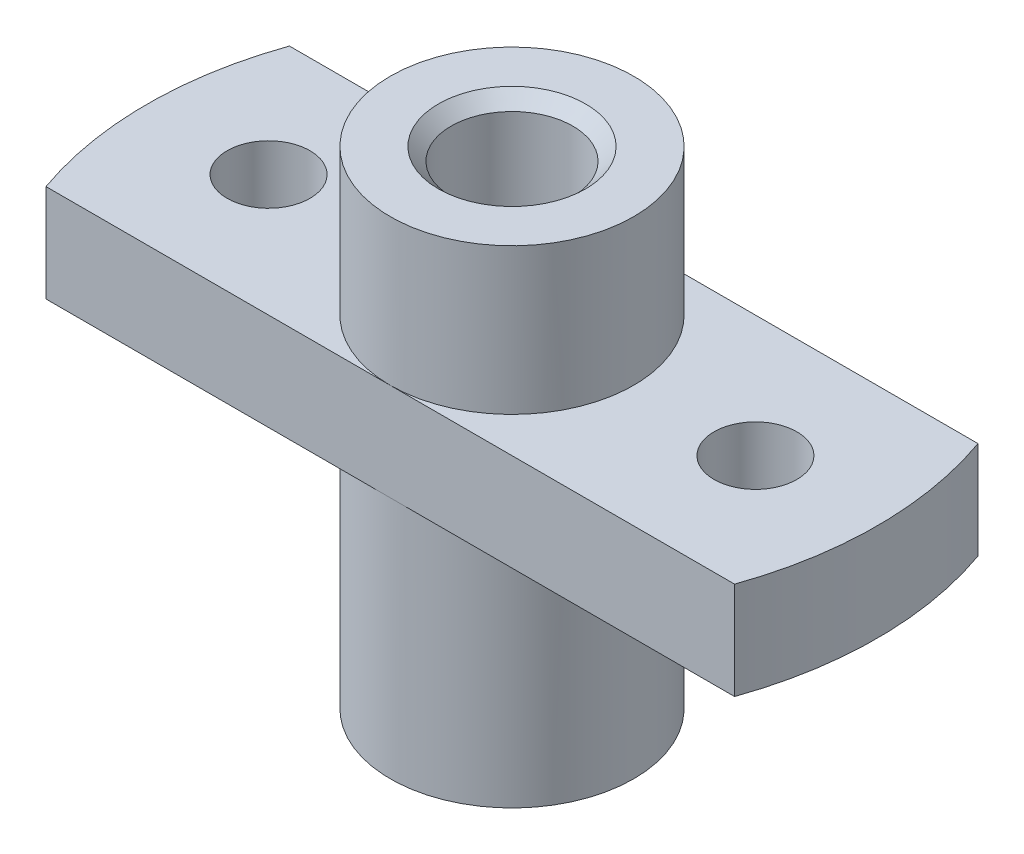
SolidWorks part; units mm, degrees
ref_plane "Front Plane" through (0, 0, 0) normal (0, 0, 1) x (1, 0, 0)
ref_plane "Top Plane" through (0, 0, 0) normal (0, 1, 0) x (1, 0, 0)
ref_plane "Right Plane" through (0, 0, 0) normal (1, 0, 0) x (0, 0, -1)
sketch "Sketch2" plane through (0, 0, 0) normal (0, 0, 1) x (1, 0, 0)
  line L0 (0, 0) -> (-5, 0)
  line L1 (-5, 0) -> (-5, 10)
  line L2 (-5, 10) -> (-15, 10)
  line L3 (-15, 10) -> (-15, 14)
  line L4 (-15, 14) -> (-5, 14)
  line L5 (-5, 14) -> (-5, 20)
  line L6 (-5, 20) -> (0, 20)
  line L7 (0, 20) -> (0, 0)
  dimension "D1" = 5
  dimension "D2" = 10
  dimension "D3" = 4
  dimension "D4" = 6
  dimension "D5" = 15
revolve "Revolve1" add sketch "Sketch2" angle 360 about L7
hole_wizard "M3 Clearance Hole1" positions "Sketch5" profile "Sketch4" hole size "M3" standard "ISO" end condition up to next
sketch "Sketch5" plane through (0, 14, 0) normal (0, 1, 0) x (-1, 0, 0)
  line L0 (-30.2348, 0) -> (30.2348, 0) construction
  line L2 (0, -14.7703) -> (0, 14.7703) construction
  point P0 (10, 0)
  point P15 (-10, 0)
  dimension "D1" = 20
sketch "Sketch4" plane through (-10, 14, 0) normal (1, 0, 0) x (0, 0, 1)
  line L0 (0, 0) -> (0, 4)
  line L1 (0, 4) -> (1.7, 4)
  line L2 (1.7, 4) -> (1.7, 0)
  line L5 (1.7, 0) -> (0, 0)
  line L11 (0, -6.35) -> (0, 107.95) construction
  dimension "Thru Hole Dia." = 3.4
  dimension "Thru Hole Depth" = 4
hole_wizard "M6 Tapped Hole1" positions "Sketch7" profile "Sketch8" tap size "M6" standard "ISO" end condition up to next
sketch "Sketch7" plane through (0, 20, 0) normal (0, 1, 0) x (-1, 0, 0)
  point P0 (0, 0)
sketch "Sketch8" plane through (0, 20, 0) normal (1, 0, 0) x (0, 0, 1)
  line L0 (0, 0) -> (0, 20)
  line L1 (0, 20) -> (3.025, 20)
  line L2 (2.5, 19.475) -> (2.5, 0.525)
  line L3 (2.5, 0.525) -> (3.025, 0)
  line L5 (3.025, 0) -> (0, 0)
  line L6 (-2.5, 0.525) -> (-3.025, 0) construction
  line L7 (3.025, 20) -> (2.5, 19.475)
  line L8 (-3.025, 20) -> (-2.5, 19.475) construction
  line L11 (0, -6.35) -> (0, 107.95) construction
  dimension "Thru Tap Drill Dia." = 5
  dimension "Thru Tap Drill Depth" = 20
  dimension "Near C'Sink Dia." = 6.05
  dimension "Near C'Sink Angle" = 90
  dimension "Far C'Sink Dia." = 6.05
  dimension "Far C'Sink Angle" = 90
cosmetic thread "Hole Thread1" parameters "D2"=6
sketch "Sketch9" plane through (0, 14, 0) normal (0, 1, 0) x (1, 0, 0)
  line L1 (-15, -5) -> (15, -5)
  line L2 (-15, -5) -> (-15, 5)
  line L3 (-15, 5) -> (15, 5)
  line L4 (15, -5) -> (15, 5)
  line L5 (-15, -5) -> (15, 5) construction
  line L6 (-15, 5) -> (15, -5) construction
  circle A1 centre (0, 0) radius 15 construction
  point P0 (0, 0)
  dimension "D1" = 10
extrude "Cut-Extrude1" cut sketch "Sketch9" against normal through all flip side to cut
